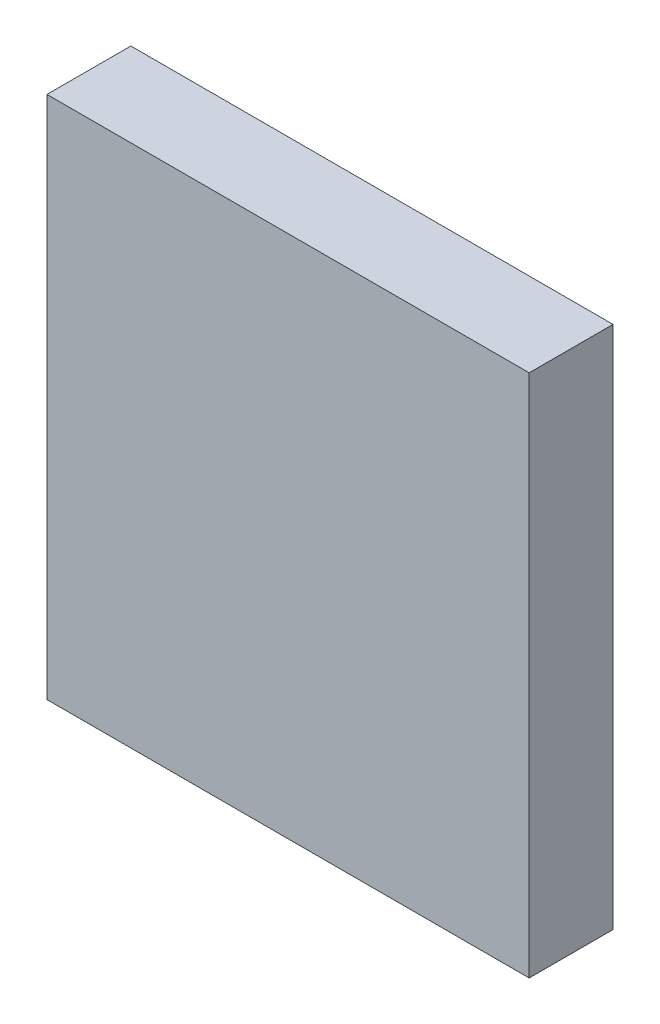
SolidWorks part; units mm, degrees
ref_plane "Front Plane" through (0, 0, 0) normal (0, 0, 1) x (1, 0, 0)
ref_plane "Top Plane" through (0, 0, 0) normal (0, 1, 0) x (1, 0, 0)
ref_plane "Right Plane" through (0, 0, 0) normal (1, 0, 0) x (0, 0, -1)
sketch "Sketch1" plane through (0, 0, 0) normal (0, 0, 1) x (1, 0, 0)
  line L1 (-19.8471, -26.0332) -> (26.1529, -26.0332)
  line L2 (-19.8471, -26.0332) -> (-19.8471, 23.9668)
  line L3 (-19.8471, 23.9668) -> (26.1529, 23.9668)
  line L4 (26.1529, -26.0332) -> (26.1529, 23.9668)
  line L5 (-19.8471, -26.0332) -> (26.1529, 23.9668) construction
  line L6 (-19.8471, 23.9668) -> (26.1529, -26.0332) construction
  point P0 (3.1529, -1.0332)
  dimension "D1" = 50
  dimension "D2" = 46
extrude "Boss-Extrude1" add sketch "Sketch1" along normal blind 8
